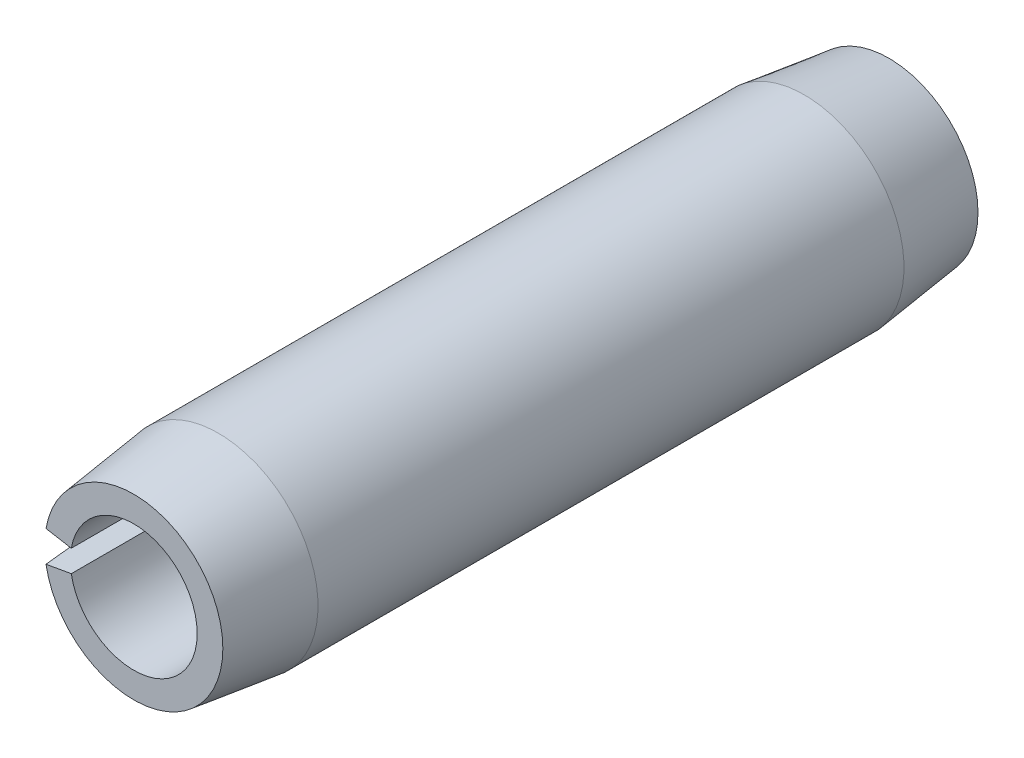
SolidWorks part; units mm, degrees
material "302 Stainless, 1/2 Hard"
ref_plane "Front Plane" through (0, 0, 0) normal (0, 0, 1) x (1, 0, 0)
ref_plane "Top Plane" through (0, 0, 0) normal (0, 1, 0) x (1, 0, 0)
ref_plane "Right Plane" through (0, 0, 0) normal (1, 0, 0) x (0, 0, -1)
sketch "Sketch1" plane through (0, 0, 0) normal (0, 0, 1) x (1, 0, 0)
  line L0 (0.5334, 0) -> (0.8382, 0) construction
  line L1 (-0.8255, 0.1456) -> (-0.5253, 0.0926)
  line L2 (-0.5253, -0.0926) -> (-0.8255, -0.1456)
  arc A0 (-0.8255, -0.1456) -> (-0.8255, 0.1456) centre (0, 0) ccw
  arc A1 (-0.5253, -0.0926) -> (-0.5253, 0.0926) centre (0, 0) ccw
  dimension "OD" = 1.6764
  dimension "Wall thickness" = 0.3048
  dimension "D3" = 20
extrude "Extrude1" add sketch "Sketch1" along normal mid plane 6.35
sketch "Sketch2" plane through (0, 0, 0) normal (1, 0, 0) x (0, 0, -1)
  line L0 (0, -0.8382) -> (0, 0.8382) construction
  line L1 (3.175, 0) -> (-3.175, 0) construction
  line L2 (3.175, -0.5334) -> (3.175, 0.5334) construction
  line L3 (3.175, 0.8382) -> (-3.175, 0.8382) construction
  line L4 (3.175, 0.8382) -> (3.175, 0.7493)
  line L5 (3.175, 0.7493) -> (2.4638, 0.8382)
  line L6 (2.4638, 0.8382) -> (3.175, 0.8382)
  line L7 (3.175, -0.8382) -> (3.175, 0.8382) construction
  line L8 (-2.4638, 0.8382) -> (-3.175, 0.8382)
  line L9 (-3.175, 0.7493) -> (-2.4638, 0.8382)
  line L10 (-3.175, 0.8382) -> (-3.175, 0.7493)
  line L11 (2.4638, -0.8382) -> (3.175, -0.8382) construction
  line L12 (3.175, -0.7493) -> (2.4638, -0.8382) construction
  line L13 (3.175, -0.8382) -> (3.175, -0.7493) construction
  dimension "B" = 1.4986
  dimension "Chamfer max" = 0.7112
revolve "Cut-Revolve1" cut sketch "Sketch2" angle 360 about L1
sketch "Sketch3" plane through (0, 0, 0) normal (0, 0, 1) x (1, 0, 0)
  line L0 (0.5334, 0) -> (0.8382, 0) construction
  line L1 (0.5334, 0) -> (0.8382, 0)
  circle A0 centre (0, 0) radius 0.8382
  circle A1 centre (0, 0) radius 0.5334
  arc A2 (-0.8255, -0.1456) -> (-0.8255, 0.1456) centre (0, 0) ccw construction
  arc A3 (-0.5253, -0.0926) -> (-0.5253, 0.0926) centre (0, 0) ccw construction
